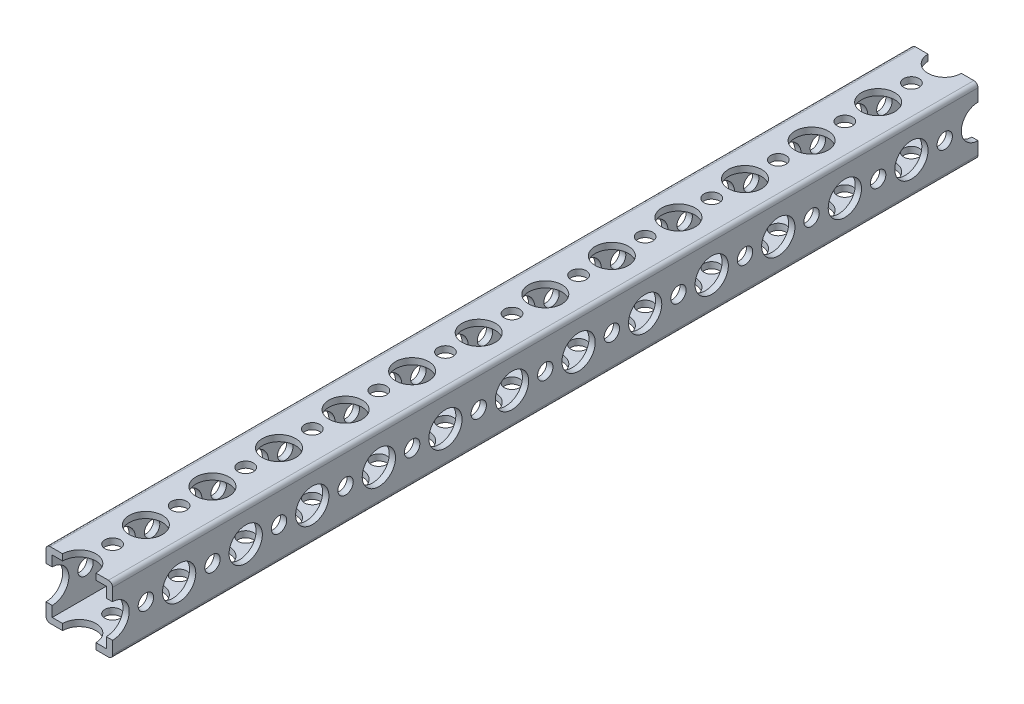
SolidWorks part; units mm, degrees
ref_plane "Front Plane" through (0, 0, 0) normal (0, 0, 1) x (1, 0, 0)
ref_plane "Top Plane" through (0, 0, 0) normal (0, 1, 0) x (1, 0, 0)
ref_plane "Right Plane" through (0, 0, 0) normal (1, 0, 0) x (0, 0, -1)
sketch "Sketch1" plane through (0, 0, 0) normal (0, 0, 1) x (1, 0, 0)
  line L1 (0, 0) -> (16, 0)
  line L2 (0, 0) -> (0, 16)
  line L3 (0, 16) -> (16, 16)
  line L4 (16, 0) -> (16, 16)
  dimension "D1" = 16
  dimension "D2" = 16
extrude "Extrude1" add sketch "Sketch1" against normal blind 208
sketch "Sketch2" plane through (0, 0, 0) normal (0, 0, 1) x (1, 0, 0)
  line L0 (-1.7793, 8) -> (18.8812, 8) construction
  line L1 (8, 16.9255) -> (8, -0.6999) construction
  line L3 (1.5, 14.5) -> (14.5, 14.5)
  line L4 (1.5, 14.5) -> (1.5, 1.5)
  line L5 (1.5, 1.5) -> (14.5, 1.5)
  line L6 (14.5, 14.5) -> (14.5, 1.5)
  line L7 (1.5, 14.5) -> (14.5, 1.5) construction
  line L8 (1.5, 1.5) -> (14.5, 14.5) construction
  point P4 (8, 8)
  dimension "D1" = 13
  dimension "D2" = 13
extrude "Extrude2" cut sketch "Sketch2" against normal through all
sketch "Sketch3" plane through (0, 16, 0) normal (0, 1, 0) x (1, 0, 0)
  line L0 (-10.6019, 48) -> (25.4979, 48) construction
  line L1 (8, -3.3001) -> (8, 305.034) construction
  line L2 (-10.6019, 80) -> (44.8988, 80) construction
  line L4 (16, 0) -> (0, 0) construction
  line L5 (-19.3069, 144) -> (85.0309, 144) construction
  circle A0 centre (8, 64) radius 4
  circle A1 centre (8, 32) radius 4
  circle A3 centre (8, 0) radius 4
  circle A4 centre (8, 96) radius 4
  circle A5 centre (8, 128) radius 4
  circle A6 centre (8, 160) radius 4
  circle A7 centre (8, 192) radius 4
  circle A8 centre (8, 224) radius 4
  circle A9 centre (8, 256) radius 4
  circle B0 centre (8, 48) radius 4
  circle B1 centre (8, 56) radius 1.85
  circle B2 centre (8, 40) radius 1.85
  circle B3 centre (8, 80) radius 4
  circle B4 centre (8, 88) radius 1.85
  circle B5 centre (8, 72) radius 1.85
  circle B6 centre (8, 16) radius 4
  circle B7 centre (8, 24) radius 1.85
  circle B8 centre (8, 8) radius 1.85
  circle B9 centre (8, 112) radius 4
  circle B10 centre (8, 120) radius 1.85
  circle B11 centre (8, 104) radius 1.85
  circle B12 centre (8, 144) radius 4
  circle B13 centre (8, 152) radius 1.85
  circle B14 centre (8, 136) radius 1.85
  circle B15 centre (8, 176) radius 4
  circle B16 centre (8, 184) radius 1.85
  circle B17 centre (8, 168) radius 1.85
  circle B18 centre (8, 208) radius 4
  circle B19 centre (8, 216) radius 1.85
  circle B20 centre (8, 200) radius 1.85
  circle B21 centre (8, 240) radius 4
  circle B22 centre (8, 248) radius 1.85
  circle B23 centre (8, 232) radius 1.85
  dimension "D1" = 24
  dimension "D2" = 16
  dimension "D4" = 16
  dimension "D5" = 32
  dimension "D7" = 16
  dimension "D13" = 48
  dimension "D3" = 24
  dimension "D6" = 64
  dimension "D8" = 48
  dimension "D9" = 32
  dimension "D10" = 64
  dimension "D11" = 96
  dimension "D14" = 16
  dimension "D15" = 80
  dimension "D16" = 112
sketch_block_instance "Block2-1"
sketch_block "Block2"
sketch_block_instance "Block2-4"
sketch_block_instance "Block2-6"
sketch_block_instance "Block2-11"
sketch_block_instance "Block2-12"
sketch_block_instance "Block2-17"
sketch_block_instance "Block2-18"
sketch_block_instance "Block2-19"
extrude "Extrude3" cut sketch "Sketch3" against normal through all
sketch "Sketch4" plane through (16, 0, 0) normal (1, 0, 0) x (0, 0, -1)
  line L0 (-4.9809, 8) -> (308.0277, 8) construction
  line L1 (48, 20.3919) -> (48, -4.2435) construction
  line L2 (0, 0) -> (0, 16) construction
  line L4 (80, -7.5844) -> (80, 23.8371) construction
  line L5 (144, 22.3836) -> (144, -28.3788) construction
  circle A0 centre (32, 8) radius 4
  circle A1 centre (64, 8) radius 4
  circle A2 centre (0, 8) radius 4
  circle A4 centre (96, 8) radius 4
  circle A5 centre (128, 8) radius 4
  circle A6 centre (160, 8) radius 4
  circle A7 centre (192, 8) radius 4
  circle A8 centre (224, 8) radius 4
  circle A9 centre (256, 8) radius 4
  circle B0 centre (48, 8.0742) radius 4
  circle B1 centre (40, 8.0742) radius 1.85
  circle B2 centre (56, 8.0742) radius 1.85
  circle B3 centre (80, 8) radius 4
  circle B4 centre (72, 8) radius 1.85
  circle B5 centre (88, 8) radius 1.85
  circle B6 centre (16, 8) radius 4
  circle B7 centre (8, 8) radius 1.85
  circle B8 centre (24, 8) radius 1.85
  circle B9 centre (112, 8) radius 4
  circle B10 centre (104, 8) radius 1.85
  circle B11 centre (120, 8) radius 1.85
  circle B12 centre (144, 8) radius 4
  circle B13 centre (136, 8) radius 1.85
  circle B14 centre (152, 8) radius 1.85
  circle B15 centre (176, 8) radius 4
  circle B16 centre (168, 8) radius 1.85
  circle B17 centre (184, 8) radius 1.85
  circle B18 centre (208, 8) radius 4
  circle B19 centre (200, 8) radius 1.85
  circle B20 centre (216, 8) radius 1.85
  circle B21 centre (240, 8) radius 4
  circle B22 centre (232, 8) radius 1.85
  circle B23 centre (248, 8) radius 1.85
  dimension "D3" = 16
  dimension "D5" = 32
  dimension "D7" = 16
  dimension "D13" = 16
  dimension "D1" = 24
  dimension "D2" = 24
  dimension "D4" = 16
  dimension "D6" = 64
  dimension "D8" = 48
  dimension "D9" = 32
  dimension "D10" = 64
  dimension "D11" = 96
  dimension "D14" = 48
  dimension "D15" = 80
  dimension "D16" = 112
sketch_block_instance "Block2-8"
sketch_block_instance "Block2-9"
sketch_block_instance "Block2-10"
sketch_block_instance "Block2-14"
sketch_block_instance "Block2-15"
sketch_block_instance "Block2-22"
sketch_block_instance "Block2-23"
sketch_block_instance "Block2-24"
extrude "Extrude4" cut sketch "Sketch4" against normal through all
fillet "Fillet1" radius 1 4 edges at (0, 0, -104) (16, 0, -104) (0, 16, -104) (16, 16, -104)
